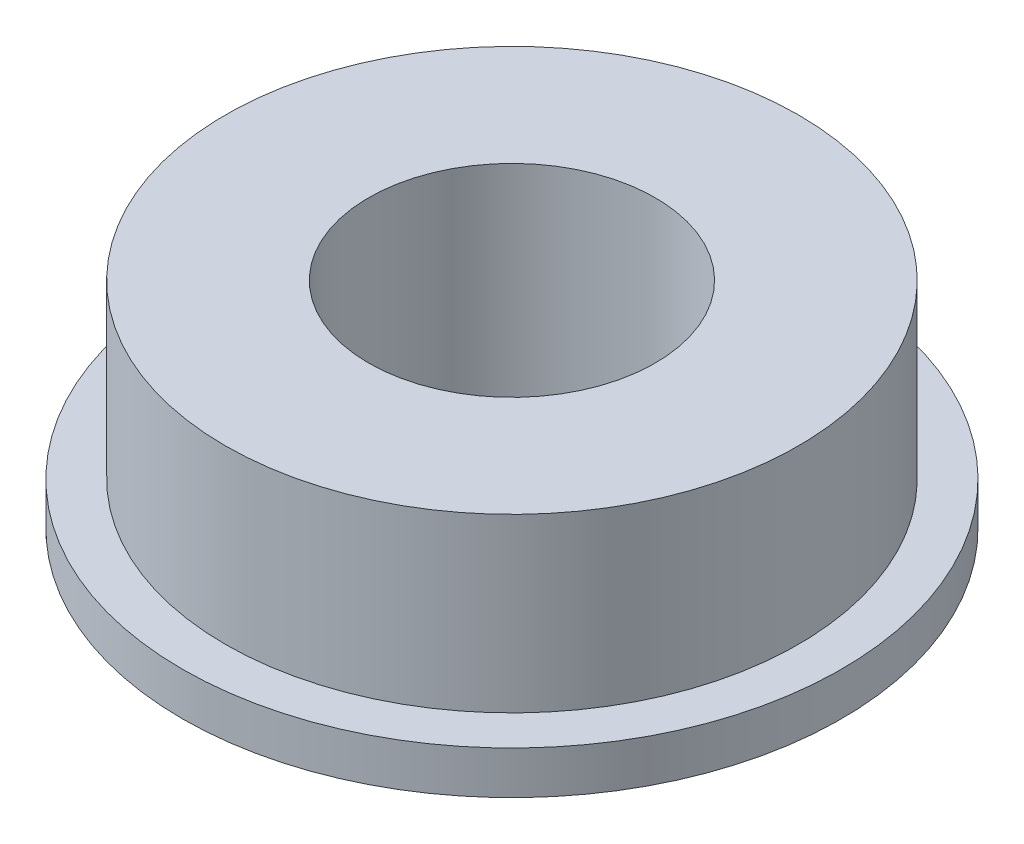
SolidWorks part; units mm, degrees
ref_plane "前基準面" through (0, 0, 0) normal (0, 0, 1) x (1, 0, 0)
ref_plane "上基準面" through (0, 0, 0) normal (0, 1, 0) x (1, 0, 0)
ref_plane "右基準面" through (0, 0, 0) normal (1, 0, 0) x (0, 0, -1)
sketch "草圖1" plane through (0, 0, 0) normal (0, 1, 0) x (1, 0, 0)
  circle A0 centre (0, 0) radius 4.6
  dimension "D1" = 9.2
extrude "填料-伸長1" add sketch "草圖1" along normal blind 0.6
sketch "草圖3" plane through (0, 0, 0) normal (0, 1, 0) x (1, 0, 0)
  circle A0 centre (0, 0) radius 4
  dimension "D1" = 8
extrude "填料-伸長2" add sketch "草圖3" along normal blind 3
sketch "草圖4" plane through (0, 3, 0) normal (0, 1, 0) x (1, 0, 0)
  circle A0 centre (0, 0) radius 2
  dimension "D1" = 4
extrude "除料-伸長1" cut sketch "草圖4" against normal through all
equation "\"D1\"= 9.2"
equation "\"D1@草圖1\"=\"D1\""
equation "\"c\"=0.6"
equation "\"D1@填料-伸長1\"=\"c\""
equation "\"D\"= 8"
equation "\"D1@草圖3\"=\"D\""
equation "\"b\"= 3"
equation "\"D1@填料-伸長2\"=\"b\""
equation "\"dd\"= 4"
equation "\"D1@草圖4\"=\"dd\""
